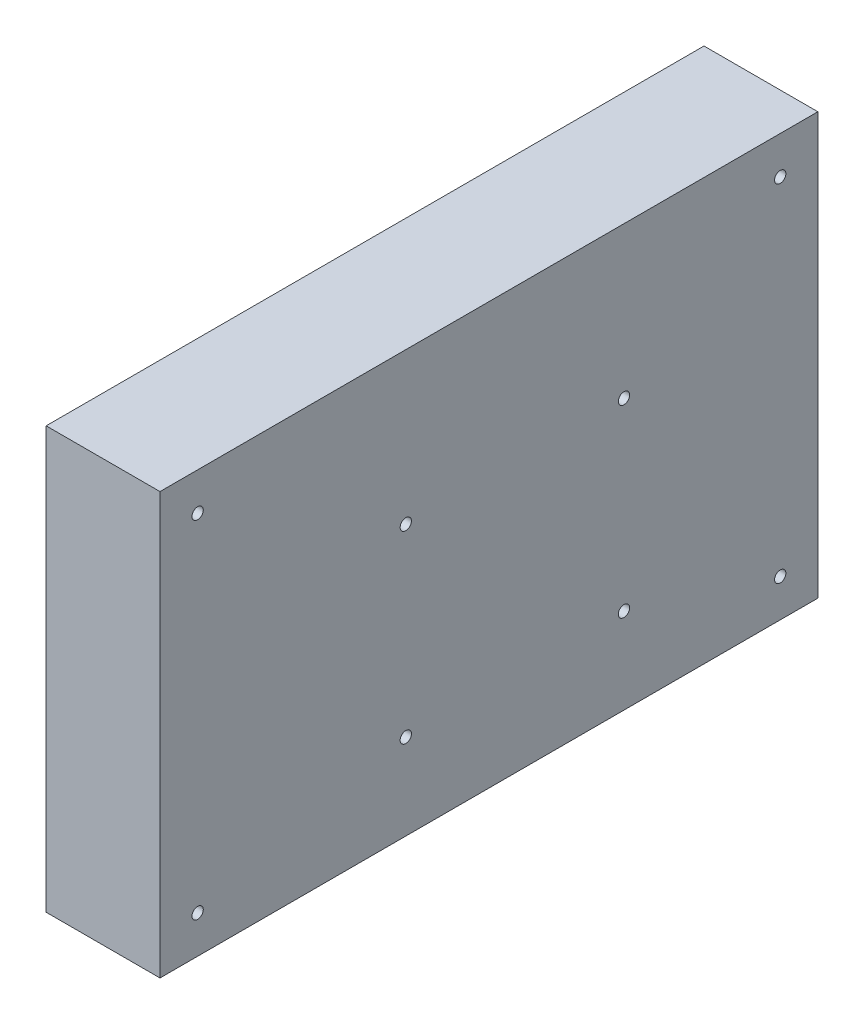
SolidWorks part; units mm, degrees
ref_plane "Alzado" through (0, 0, 0) normal (0, 0, 1) x (1, 0, 0)
ref_plane "Planta" through (0, 0, 0) normal (0, 1, 0) x (1, 0, 0)
ref_plane "Vista lateral" through (0, 0, 0) normal (1, 0, 0) x (0, 0, -1)
sketch "Croquis1" plane through (0, 0, 0) normal (1, 0, 0) x (0, 0, -1)
  line L1 (82.45, -51) -> (-82.45, -51)
  line L2 (82.45, -51) -> (82.45, 51)
  line L3 (82.45, 51) -> (-82.45, 51)
  line L4 (-82.45, -51) -> (-82.45, 51)
  point P0 (0, 0)
  point P5 (0, 0)
  dimension "D1" = 102
  dimension "D2" = 164.9
extrude "Saliente-Extruir2" add sketch "Croquis1" along normal blind 14.27
sketch "Croquis2" plane through (0, 0, 0) normal (1, 0, 0) x (0, 0, -1)
  line L0 (82.45, -51) -> (82.45, 51) construction
  line L5 (87.45, 56) -> (-87.45, 56)
  line L6 (87.45, 56) -> (87.45, -56)
  line L7 (87.45, -56) -> (-87.45, -56)
  line L8 (-87.45, 56) -> (-87.45, -56)
  line L9 (-82.45, 51) -> (-82.45, -51) construction
  line L10 (82.45, 51) -> (-82.45, 51) construction
  line L11 (-82.45, -51) -> (82.45, -51) construction
  line L13 (83.45, 52) -> (-83.45, 52)
  line L14 (83.45, 52) -> (83.45, -52)
  line L15 (83.45, -52) -> (-83.45, -52)
  line L16 (-83.45, 52) -> (-83.45, -52)
  dimension "D1" = 5
  dimension "D2" = 5
  dimension "D3" = 5
  dimension "D4" = 5
  dimension "D5" = 1
  dimension "D6" = 1
  dimension "D7" = 1
  dimension "D8" = 1
extrude "Saliente-Extruir3" add sketch "Croquis2" along normal blind 14.27 separate body
sketch "Croquis3" plane through (0, 0, 0) normal (-1, 0, 0) x (0, 0, 1)
  line L0 (83.45, 52) -> (83.45, -52) construction
  line L1 (-87.45, 56) -> (87.45, 56)
  line L2 (-87.45, 56) -> (-87.45, -56)
  line L3 (-87.45, -56) -> (87.45, -56)
  line L4 (87.45, 56) -> (87.45, -56)
  line L5 (-80.45, 49.125) -> (80.45, 49.125)
  line L6 (-80.45, 49.125) -> (-80.45, -49.2494)
  line L7 (-80.45, -49.2494) -> (80.45, -49.2494)
  line L8 (80.45, 49.125) -> (80.45, -49.2494)
  line L9 (-83.45, -52) -> (-83.45, 52) construction
  line L10 (-83.45, 52) -> (83.45, 52) construction
  line L11 (83.45, -52) -> (-83.45, -52) construction
  dimension "D1" = 160.9
  dimension "D2" = 3
  dimension "D3" = 3
  dimension "D4" = 2.875
  dimension "D5" = 2.7506
extrude "Saliente-Extruir5" add sketch "Croquis3" along normal blind 1
sketch "Croquis4" plane through (14.27, 0, 0) normal (1, 0, 0) x (0, 0, -1)
  line L1 (-82.45, 51) -> (82.45, 51)
  line L2 (-82.45, 51) -> (-82.45, -51)
  line L3 (-82.45, -51) -> (82.45, -51)
  line L4 (82.45, 51) -> (82.45, -51)
extrude "Cortar-Extruir2" cut sketch "Croquis4" against normal blind 14.27
sketch "Croquis6" plane through (14.27, 0, 0) normal (1, 0, 0) x (0, 0, -1)
  line L1 (-87.45, 56) -> (87.45, 56)
  line L2 (-87.45, 56) -> (-87.45, -56)
  line L3 (-87.45, -56) -> (87.45, -56)
  line L4 (87.45, 56) -> (87.45, -56)
  circle A0 centre (-77.445, 46) radius 1.5
  circle A1 centre (-77.445, -46) radius 1.5
  circle A2 centre (-22.1, 15.81) radius 1.5
  circle A3 centre (35.9, 15.81) radius 1.5
  circle A4 centre (-22.1, -33.19) radius 1.5
  circle A5 centre (35.9, -33.19) radius 1.5
  circle A6 centre (77.445, 46) radius 1.5
  circle A7 centre (77.445, -46) radius 1.5
  dimension "D1" = 3
  dimension "D2" = 3
extrude "Saliente-Extruir6" add sketch "Croquis6" along normal blind 15
sketch "Croquis8" plane through (14.27, 0, 0) normal (-1, 0, 0) x (0, 0, 1)
  line L1 (-80.45, 49.125) -> (80.45, 49.125)
  line L2 (-80.45, 49.125) -> (-80.45, -49.2494)
  line L3 (-80.45, -49.2494) -> (80.45, -49.2494)
  line L4 (80.45, 49.125) -> (80.45, -49.2494)
extrude "Cortar-Extruir3" cut sketch "Croquis8" against normal blind 9
sketch "Croquis9" plane through (14.27, 0, 0) normal (-1, 0, 0) x (0, 0, 1)
  line L1 (-83.45, 52) -> (83.45, 52)
  line L2 (-83.45, 52) -> (-83.45, -52)
  line L3 (-83.45, -52) -> (83.45, -52)
  line L4 (83.45, 52) -> (83.45, -52)
extrude "Cortar-Extruir5" cut sketch "Croquis9" against normal blind 11
